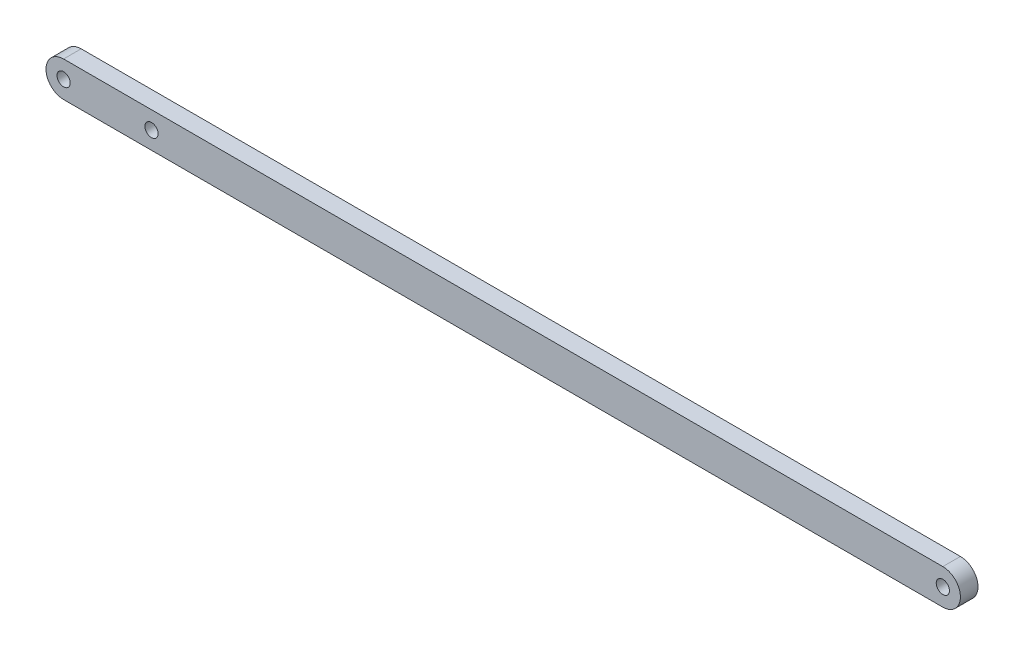
SolidWorks part; units mm, degrees
ref_plane "Front Plane" through (0, 0, 0) normal (0, 0, 1) x (1, 0, 0)
ref_plane "Top Plane" through (0, 0, 0) normal (0, 1, 0) x (1, 0, 0)
ref_plane "Right Plane" through (0, 0, 0) normal (1, 0, 0) x (0, 0, -1)
sketch "Sketch1" plane through (0, 0, 0) normal (0, 0, 1) x (1, 0, 0)
  line L0 (159.7576, 0) -> (-40.2424, 0) construction
  line L1 (159.7576, -4) -> (-40.2424, -4)
  line L2 (159.7576, 4) -> (-40.2424, 4)
  arc A0 (159.7576, -4) -> (159.7576, 4) centre (159.7576, 0) ccw
  arc A1 (-40.2424, 4) -> (-40.2424, -4) centre (-40.2424, 0) ccw
  circle A2 centre (-20.2424, 0) radius 1.5
  circle A3 centre (-40.2424, 0) radius 1.5
  circle A4 centre (159.7576, 0) radius 1.5
  point P3 (59.7576, 0)
  dimension "D1" = 4
  dimension "D3" = 3
  dimension "D4" = 20
  dimension "D2" = 200
extrude "Boss-Extrude1" add sketch "Sketch1" along normal blind 4
